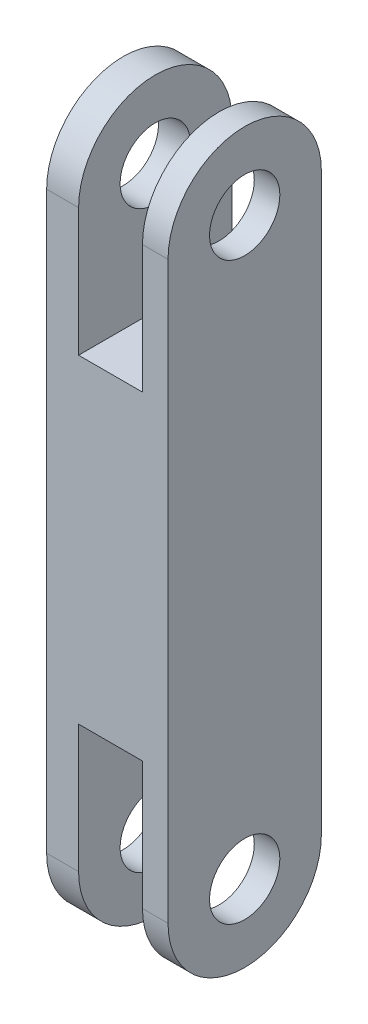
SolidWorks part; units mm, degrees
ref_plane "Front Plane" through (0, 0, 0) normal (1, 0, 0) x (0, 1, 0)
ref_plane "Top Plane" through (0, 0, 0) normal (0, 0, 1) x (0, 1, 0)
ref_plane "Right Plane" through (0, 0, 0) normal (0, 1, 0) x (-1, 0, 0)
sketch "Sketch1" plane through (0, 0, 0) normal (1, 0, 0) x (0, 1, 0)
  line L0 (0, 0) -> (77.8257, 0) construction
  line L1 (0, 6) -> (45, 6)
  line L2 (0, -6) -> (45, -6)
  circle A0 centre (0, 0) radius 2.75
  arc A1 (0, 6) -> (0, -6) centre (0, 0) ccw
  circle A2 centre (45, 0) radius 2.75
  arc A3 (45, -6) -> (45, 6) centre (45, 0) ccw
  dimension "D1" = 5.5
  dimension "D2" = 12
  dimension "D3" = 5.5
  dimension "D4" = 12
  dimension "D5" = 45
extrude "Boss-Extrude1" add sketch "Sketch1" along normal blind 2
sketch "Sketch2" plane through (0, 0, 0) normal (0, 0, 1) x (0, 1, 0)
  line L0 (-10.937, 2.5) -> (52.1419, 2.5) construction
  line L1 (45, 0) -> (0, 0) construction
  dimension "D1" = 2.5
sketch "Sketch3" plane through (0, 0, 0) normal (-1, 0, 0) x (0, -1, 0)
  line L0 (-45, 6) -> (0, 6) construction
  line L1 (-35, 6) -> (-10, 6)
  line L2 (-35, 6) -> (-35, -6)
  line L3 (-35, -6) -> (-10, -6)
  line L4 (-10, 6) -> (-10, -6)
  line L5 (0, -6) -> (-45, -6) construction
  arc A0 (-45, 6) -> (-45, -6) centre (-45, 0) ccw construction
  arc A1 (0, -6) -> (0, 6) centre (0, 0) ccw construction
  dimension "D1" = 10
  dimension "D2" = 10
extrude "Boss-Extrude2" add sketch "Sketch3" along normal blind 5
sketch "Sketch4" plane through (-5, 0, 0) normal (-1, 0, 0) x (0, -1, 0)
  line L0 (-45, 6) -> (0, 6)
  line L1 (-45, -6) -> (0, -6)
  circle A0 centre (-45, 0) radius 2.75
  arc A1 (-45, 6) -> (-45, -6) centre (-45, 0) ccw
  circle A2 centre (0, 0) radius 2.75
  arc A3 (0, -6) -> (0, 6) centre (0, 0) ccw
extrude "Boss-Extrude3" add sketch "Sketch4" along normal blind 2.5
